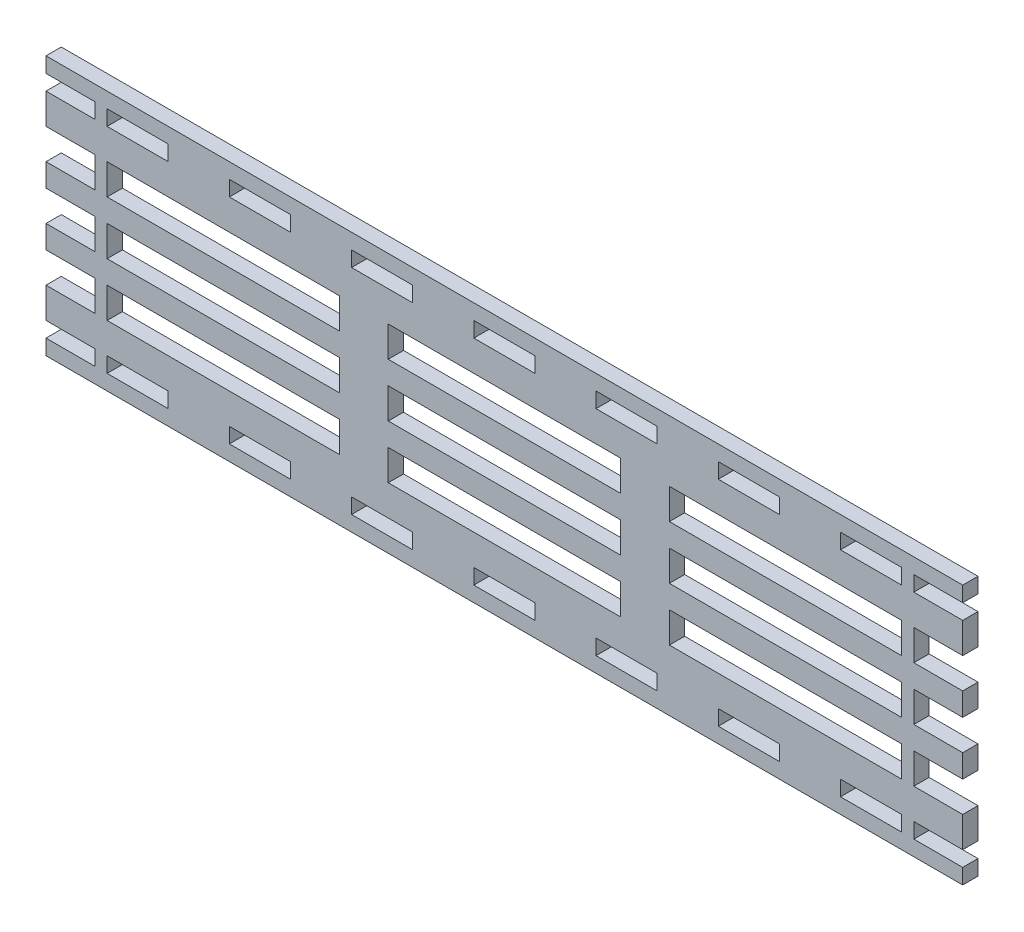
SolidWorks part; units mm, degrees
material "Maple"
ref_plane "Front Plane" through (0, 0, 0) normal (0, 0, 1) x (1, 0, 0)
ref_plane "Top Plane" through (0, 0, 0) normal (0, 1, 0) x (1, 0, 0)
ref_plane "Right Plane" through (0, 0, 0) normal (1, 0, 0) x (0, 0, -1)
sketch "Sketch1" plane through (0, 0, 0) normal (0, 0, 1) x (1, 0, 0)
  line L0 (-75, 11.25) -> (0, 11.25) construction
  line L1 (-75, -21.25) -> (75, -21.25) construction
  line L2 (-75, -21.25) -> (-75, 21.25) construction
  line L3 (-75, 21.25) -> (75, 21.25) construction
  line L4 (75, -21.25) -> (75, 21.25) construction
  line L5 (-75, -21.25) -> (75, 21.25) construction
  line L6 (-75, 21.25) -> (75, -21.25) construction
  line L9 (0, -10) -> (0, 21.25) construction
  line L10 (-75, 6.25) -> (0, 6.25) construction
  line L11 (-19, 11.25) -> (-19, 6.25)
  line L12 (-75, 18.75) -> (0, 18.75) construction
  line L13 (75, 18.75) -> (0, 18.75) construction
  line L14 (-75, 16.25) -> (0, 16.25) construction
  line L15 (75, 16.25) -> (0, 16.25) construction
  line L16 (-75, 2.5) -> (0, 2.5) construction
  line L18 (-75, 6.25) -> (-75, 2.5)
  line L20 (-75, -2.5) -> (-75, -6.25)
  line L22 (75, -2.5) -> (75, -6.25)
  line L24 (-19, 11.25) -> (19, 11.25)
  line L26 (19, 11.25) -> (19, 6.25)
  line L44 (-19, 6.25) -> (19, 6.25)
  line L45 (-19, 2.5) -> (-19, -2.5)
  line L46 (-19, -2.5) -> (19, -2.5)
  line L47 (19, 2.5) -> (19, -2.5)
  line L48 (-12.6127, -18.75) -> (16.4628, -18.75) construction
  line L49 (-12.6127, -16.25) -> (16.4628, -16.25) construction
  line L50 (-12.6127, -13.75) -> (16.4628, -13.75) construction
  line L51 (-12.6127, -11.25) -> (16.4628, -11.25) construction
  line L52 (-27, 0) -> (29.3489, 0) construction
  line L53 (-5, -18.75) -> (5, -18.75)
  line L54 (-5, -18.75) -> (-5, -16.25)
  line L55 (-5, -16.25) -> (5, -16.25)
  line L56 (5, -18.75) -> (5, -16.25)
  line L57 (-5, -18.75) -> (5, -16.25) construction
  line L58 (-5, -16.25) -> (5, -18.75) construction
  line L59 (-5, 16.25) -> (5, 16.25)
  line L60 (5, 18.75) -> (5, 16.25)
  line L61 (-5, 18.75) -> (5, 18.75)
  line L62 (-5, 18.75) -> (-5, 16.25)
  line L63 (15, 16.25) -> (25, 16.25)
  line L64 (25, 18.75) -> (25, 16.25)
  line L65 (15, 18.75) -> (25, 18.75)
  line L66 (15, 18.75) -> (15, 16.25)
  line L67 (15, -18.75) -> (25, -18.75)
  line L68 (25, -18.75) -> (25, -16.25)
  line L69 (15, -16.25) -> (25, -16.25)
  line L70 (15, -18.75) -> (15, -16.25)
  line L71 (35, 16.25) -> (45, 16.25)
  line L72 (45, 18.75) -> (45, 16.25)
  line L73 (35, 18.75) -> (45, 18.75)
  line L74 (35, 18.75) -> (35, 16.25)
  line L75 (35, -18.75) -> (45, -18.75)
  line L76 (45, -18.75) -> (45, -16.25)
  line L77 (35, -16.25) -> (45, -16.25)
  line L78 (35, -18.75) -> (35, -16.25)
  line L79 (55, 16.25) -> (65, 16.25)
  line L80 (65, 18.75) -> (65, 16.25)
  line L81 (55, 18.75) -> (65, 18.75)
  line L82 (55, 18.75) -> (55, 16.25)
  line L83 (55, -18.75) -> (65, -18.75)
  line L84 (65, -18.75) -> (65, -16.25)
  line L85 (55, -16.25) -> (65, -16.25)
  line L86 (55, -18.75) -> (55, -16.25)
  line L87 (-25, -18.75) -> (-15, -18.75)
  line L88 (-15, -18.75) -> (-15, -16.25)
  line L89 (-25, -16.25) -> (-15, -16.25)
  line L90 (-25, -18.75) -> (-25, -16.25)
  line L91 (-25, 16.25) -> (-15, 16.25)
  line L92 (-15, 18.75) -> (-15, 16.25)
  line L93 (-25, 18.75) -> (-15, 18.75)
  line L94 (-25, 18.75) -> (-25, 16.25)
  line L95 (-45, -18.75) -> (-35, -18.75)
  line L96 (-35, -18.75) -> (-35, -16.25)
  line L97 (-45, -16.25) -> (-35, -16.25)
  line L98 (-45, -18.75) -> (-45, -16.25)
  line L99 (-45, 16.25) -> (-35, 16.25)
  line L100 (-35, 18.75) -> (-35, 16.25)
  line L101 (-45, 18.75) -> (-35, 18.75)
  line L102 (-45, 18.75) -> (-45, 16.25)
  line L103 (-65, -18.75) -> (-55, -18.75)
  line L104 (-55, -18.75) -> (-55, -16.25)
  line L105 (-65, -16.25) -> (-55, -16.25)
  line L106 (-65, -18.75) -> (-65, -16.25)
  line L107 (-65, 16.25) -> (-55, 16.25)
  line L108 (-55, 18.75) -> (-55, 16.25)
  line L109 (-65, 18.75) -> (-55, 18.75)
  line L110 (-65, 18.75) -> (-65, 16.25)
  line L111 (-67, 21.25) -> (-67, -21.25) construction
  line L112 (67, 21.25) -> (67, -21.25) construction
  line L113 (75, 21.25) -> (-75, 21.25)
  line L114 (-75, 21.25) -> (-75, 18.75)
  line L115 (-75, 18.75) -> (-67, 18.75)
  line L116 (-67, 18.75) -> (-67, 16.25)
  line L117 (-67, 16.25) -> (-75, 16.25)
  line L118 (-75, 16.25) -> (-75, 11.25)
  line L119 (-75, 11.25) -> (-67, 11.25)
  line L120 (-67, 11.25) -> (-67, 6.25)
  line L121 (-67, 6.25) -> (-75, 6.25)
  line L124 (-67, 2.5) -> (-67, -2.5)
  line L125 (-67, -2.5) -> (-75, -2.5)
  line L139 (-67, -6.25) -> (-75, -6.25)
  line L140 (-67, -11.25) -> (-67, -6.25)
  line L141 (-75, -11.25) -> (-67, -11.25)
  line L142 (-75, -16.25) -> (-75, -11.25)
  line L143 (-67, -16.25) -> (-75, -16.25)
  line L144 (-67, -18.75) -> (-67, -16.25)
  line L145 (-75, -18.75) -> (-67, -18.75)
  line L146 (-75, -21.25) -> (-75, -18.75)
  line L147 (75, -21.25) -> (-75, -21.25)
  line L148 (-19, 2.5) -> (19, 2.5)
  line L149 (-19, -6.25) -> (19, -6.25)
  line L150 (19, -11.25) -> (19, -6.25)
  line L151 (-19, -11.25) -> (19, -11.25)
  line L152 (-19, -11.25) -> (-19, -6.25)
  line L228 (75, -21.25) -> (75, -18.75)
  line L229 (75, -18.75) -> (67, -18.75)
  line L230 (67, -18.75) -> (67, -16.25)
  line L231 (67, -16.25) -> (75, -16.25)
  line L232 (75, -16.25) -> (75, -11.25)
  line L233 (75, -11.25) -> (67, -11.25)
  line L234 (67, -11.25) -> (67, -6.25)
  line L235 (67, -6.25) -> (75, -6.25)
  line L249 (67, -2.5) -> (75, -2.5)
  line L250 (67, 2.5) -> (67, -2.5)
  line L251 (75, 2.5) -> (67, 2.5)
  line L252 (75, 6.25) -> (75, 2.5)
  line L253 (67, 6.25) -> (75, 6.25)
  line L254 (67, 11.25) -> (67, 6.25)
  line L255 (75, 11.25) -> (67, 11.25)
  line L256 (75, 16.25) -> (75, 11.25)
  line L257 (67, 16.25) -> (75, 16.25)
  line L258 (67, 18.75) -> (67, 16.25)
  line L259 (75, 18.75) -> (67, 18.75)
  line L260 (75, 21.25) -> (75, 18.75)
  line L263 (-65, 21.25) -> (-65, -21.25) construction
  line L264 (-27, 21.25) -> (-27, 1.25) construction
  line L265 (-65, 2.5) -> (-65, -2.5)
  line L266 (-65, 11.25) -> (-27, 11.25)
  line L267 (-65, 11.25) -> (-65, 6.25)
  line L273 (-65, 6.25) -> (-27, 6.25)
  line L274 (-27, 11.25) -> (-27, 6.25)
  line L275 (-65, 2.5) -> (-27, 2.5)
  line L278 (-27, 2.5) -> (-27, -2.5)
  line L279 (-65, -2.5) -> (-27, -2.5)
  line L295 (-65, -6.25) -> (-27, -6.25)
  line L296 (-27, -11.25) -> (-27, -6.25)
  line L297 (-65, -11.25) -> (-27, -11.25)
  line L298 (-65, -11.25) -> (-65, -6.25)
  line L299 (65, 6.25) -> (27, 6.25)
  line L300 (27, 11.25) -> (27, 6.25)
  line L301 (65, 11.25) -> (27, 11.25)
  line L302 (65, 11.25) -> (65, 6.25)
  line L303 (65, 2.5) -> (27, 2.5)
  line L304 (27, 2.5) -> (27, -2.5)
  line L305 (65, -2.5) -> (27, -2.5)
  line L306 (65, 2.5) -> (65, -2.5)
  line L319 (65, -11.25) -> (65, -6.25)
  line L320 (65, -11.25) -> (27, -11.25)
  line L321 (27, -11.25) -> (27, -6.25)
  line L322 (65, -6.25) -> (27, -6.25)
  line L344 (-75, -21.25) -> (-75, -18.75)
  line L345 (-75, -18.75) -> (-67, -18.75)
  line L346 (-67, -18.75) -> (-67, -16.25)
  line L347 (-67, -16.25) -> (-75, -16.25)
  line L348 (-75, -16.25) -> (-75, -11.25)
  line L349 (-75, -11.25) -> (-67, -11.25)
  line L350 (-67, -11.25) -> (-67, -6.25)
  line L351 (-67, -6.25) -> (-75, -6.25)
  line L365 (-67, -2.5) -> (-75, -2.5)
  line L366 (-67, 2.5) -> (-67, -2.5)
  line L367 (-75, 2.5) -> (-67, 2.5)
  line L369 (-67, 6.25) -> (-75, 6.25)
  line L370 (-67, 11.25) -> (-67, 6.25)
  line L371 (-75, 11.25) -> (-67, 11.25)
  line L372 (-75, 16.25) -> (-75, 11.25)
  line L373 (-67, 16.25) -> (-75, 16.25)
  line L374 (-67, 18.75) -> (-67, 16.25)
  line L375 (-75, 18.75) -> (-67, 18.75)
  line L376 (-75, 21.25) -> (-75, 18.75)
  line L377 (75, 21.25) -> (75, 18.75)
  line L378 (75, 18.75) -> (67, 18.75)
  line L379 (67, 18.75) -> (67, 16.25)
  line L380 (67, 16.25) -> (75, 16.25)
  line L381 (75, 16.25) -> (75, 11.25)
  line L382 (75, 11.25) -> (67, 11.25)
  line L383 (67, 11.25) -> (67, 6.25)
  line L384 (67, 6.25) -> (75, 6.25)
  line L385 (75, 6.25) -> (75, 2.5)
  line L386 (75, 2.5) -> (67, 2.5)
  line L387 (67, 2.5) -> (67, -2.5)
  line L388 (67, -2.5) -> (75, -2.5)
  line L402 (67, -6.25) -> (75, -6.25)
  line L403 (67, -11.25) -> (67, -6.25)
  line L404 (75, -11.25) -> (67, -11.25)
  line L405 (75, -16.25) -> (75, -11.25)
  line L406 (67, -16.25) -> (75, -16.25)
  line L407 (67, -18.75) -> (67, -16.25)
  line L408 (75, -18.75) -> (67, -18.75)
  line L409 (75, -21.25) -> (75, -18.75)
  point P0 (0, 0)
  point P23 (0, -17.5)
  point P159 (-75, 0)
  point P255 (0, -21.25)
  point P285 (0, 21.25)
  dimension "D3" = 2.5
  dimension "D1" = 42.5
  dimension "D2" = 150
  dimension "D4" = 5
  dimension "D5" = 2.5
  dimension "D7" = 2.5
  dimension "D10" = 10
  dimension "D12" = 10
  dimension "D14" = 10
  dimension "D15" = 2
  dimension "D16" = 2.5
  dimension "D17" = 2.5
  dimension "D18" = 2
  dimension "D19" = 2
  dimension "D8" = 5
  dimension "D20" = 8
  dimension "D6" = 2
  dimension "D9" = 4
  dimension "D11" = 4
  dimension "D13" = 4
  dimension "D21" = 2
extrude "Boss-Extrude1" add sketch "Sketch1" along normal mid plane 2.5
